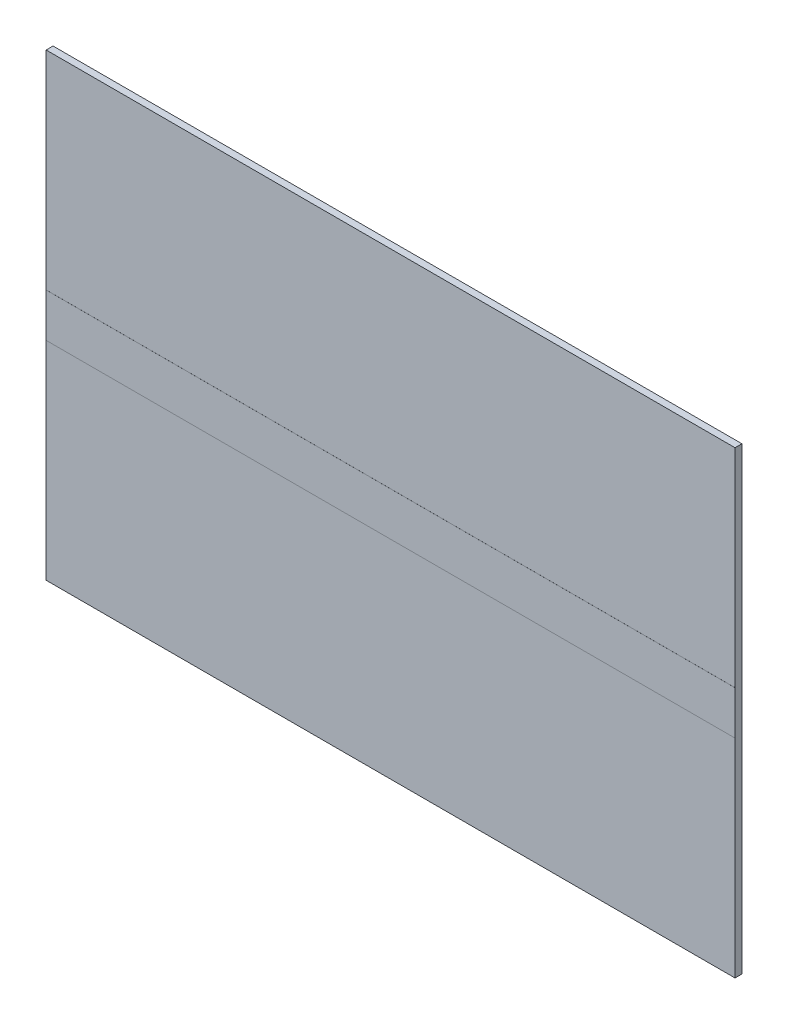
SolidWorks part; units mm, degrees
ref_plane "Płaszczyzna przednia" through (0, 0, 0) normal (0, 0, 1) x (1, 0, 0)
ref_plane "Płaszczyzna górna" through (0, 0, 0) normal (0, 1, 0) x (1, 0, 0)
ref_plane "Płaszczyzna prawa" through (0, 0, 0) normal (1, 0, 0) x (0, 0, -1)
sketch "Szkic1" plane through (0, 0, 0) normal (0, 0, 1) x (1, 0, 0)
  line L1 (0, 0) -> (300, 0)
  line L2 (0, 0) -> (0, 200)
  line L3 (0, 200) -> (300, 200)
  line L4 (300, 0) -> (300, 200)
  dimension "D1" = 300
  dimension "D2" = 200
extrude "Dodanie-wyciągnięcie1" add sketch "Szkic1" along normal blind 3
sketch "Szkic2" plane through (0, 0, 3) normal (0, 0, 1) x (1, 0, 0)
  line L0 (0, 109.5) -> (300, 109.5)
  line L1 (0, 200) -> (0, 0) construction
  line L2 (300, 0) -> (300, 200) construction
  line L3 (0, 90.5) -> (300, 90.5)
  line L4 (-28.5622, 100) -> (0, 100) construction
  line L5 (0, 100) -> (375.7947, 100) construction
  line L6 (0, 109.5) -> (0, 90.5)
  line L7 (300, 109.5) -> (300, 90.5)
  dimension "D1" = 19
extrude "Dodanie-wyciągnięcie2" add sketch "Szkic2" along normal blind 0.02
